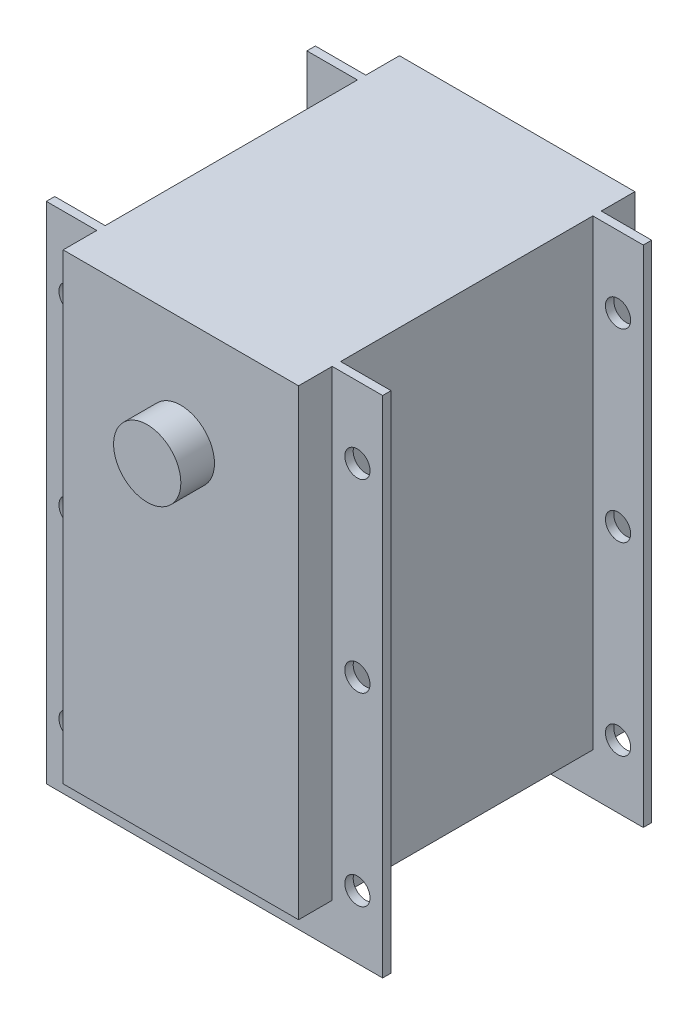
SolidWorks part; units mm, degrees
ref_plane "Front Plane" through (0, 0, 0) normal (0, 0, 1) x (1, 0, 0)
ref_plane "Top Plane" through (0, 0, 0) normal (0, 1, 0) x (1, 0, 0)
ref_plane "Right Plane" through (0, 0, 0) normal (1, 0, 0) x (0, 0, -1)
sketch "Sketch1" plane through (0, 0, 0) normal (0, 0, 1) x (1, 0, 0)
  line L1 (-14, 27.5) -> (14, 27.5)
  line L2 (-14, 27.5) -> (-14, -27.5)
  line L3 (-14, -27.5) -> (14, -27.5)
  line L4 (14, 27.5) -> (14, -27.5)
  dimension "D1" = 55
  dimension "D2" = 27.5
  dimension "D3" = 28
  dimension "D4" = 14
extrude "Boss-Extrude1" add sketch "Sketch1" along normal blind 40
ref_plane "Plane1" through (0, 0, 36) normal (0, 0, 1) x (1, 0, 0)
sketch "Sketch3" plane through (0, 0, 36) normal (0, 0, 1) x (1, 0, 0)
  line L0 (14, 27.5) -> (-14, 27.5) construction
  line L1 (-20, 27.5) -> (20, 27.5)
  line L2 (-20, 27.5) -> (-20, -32.5)
  line L3 (-20, -32.5) -> (20, -32.5)
  line L4 (20, 27.5) -> (20, -32.5)
  line L5 (-14, -27.5) -> (14, -27.5) construction
  dimension "D1" = 40
  dimension "D2" = 20
  dimension "D3" = 0
  dimension "D4" = 5
extrude "Boss-Extrude2" add sketch "Sketch3" against normal blind 1
ref_plane "Plane2" through (0, 0, 4) normal (0, 0, -1) x (-1, 0, 0)
sketch "Sketch4" plane through (0, 0, 4) normal (0, 0, -1) x (-1, 0, 0)
  line L1 (-20, 27.5) -> (20, 27.5)
  line L2 (-20, 27.5) -> (-20, -32.5)
  line L3 (-20, -32.5) -> (20, -32.5)
  line L4 (20, 27.5) -> (20, -32.5)
extrude "Boss-Extrude3" add sketch "Sketch4" against normal blind 1
sketch "Sketch5" plane through (0, 0, 36) normal (0, 0, 1) x (1, 0, 0)
  line L1 (20, 27.5) -> (14, 27.5) construction
  line L3 (-20, 27.5) -> (-20, -32.5) construction
  line L4 (-14, 27.5) -> (-20, 27.5) construction
  line L5 (20, -32.5) -> (20, 27.5) construction
  circle A0 centre (-17, 19) radius 1.5
  circle A1 centre (17, 19) radius 1.5
  circle A2 centre (-17, -3) radius 1.5
  circle A3 centre (17, -3) radius 1.5
  circle A4 centre (17, -25) radius 1.5
  circle A5 centre (-17, -25) radius 1.5
  point P2 (-17, 17.5)
  point P3 (-17, 27.5)
  point P13 (17, 17.5)
  dimension "D1" = 3
  dimension "D2" = 8.5
  dimension "D3" = 3
  dimension "D6" = 3
  dimension "D8" = 3
  dimension "D9" = 3
  dimension "D11" = 3
  dimension "D4" = 3
  dimension "D5" = 3
  dimension "D7" = 22
  dimension "D10" = 22
  dimension "D12" = 22
  dimension "D13" = 10
  dimension "D14" = 22
extrude "Cut-Extrude1" cut sketch "Sketch5" against normal through all
sketch "Sketch6" plane through (0, 0, 40) normal (0, 0, 1) x (1, 0, 0)
  line L0 (14, 27.5) -> (-14, 27.5) construction
  circle A0 centre (0, 14.5) radius 4
  dimension "D1" = 8
  dimension "D2" = 13
extrude "Boss-Extrude4" add sketch "Sketch6" along normal blind 4
sketch "Sketch7" plane through (0, 0, 0) normal (0, 0, -1) x (-1, 0, 0)
  line L0 (-14, 27.5) -> (14, 27.5) construction
  circle A0 centre (0, 13.5) radius 3.5
  dimension "D2" = 7
  dimension "D1" = 14
extrude "Boss-Extrude5" add sketch "Sketch7" along normal blind 1
